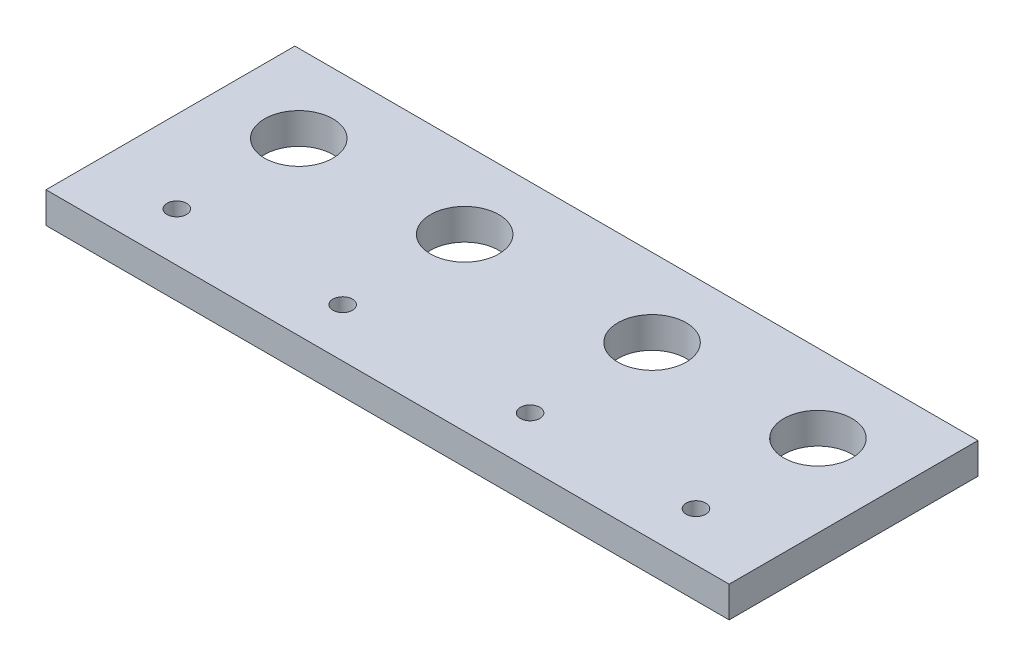
SolidWorks part; units mm, degrees
ref_plane "Front" through (0, 0, 0) normal (0, 0, 1) x (1, 0, 0)
ref_plane "Top" through (0, 0, 0) normal (0, 1, 0) x (1, 0, 0)
ref_plane "Right" through (0, 0, 0) normal (1, 0, 0) x (0, 0, -1)
sketch "Sketch1" plane through (0, 0, 0) normal (0, 1, 0) x (1, 0, 0)
  line L0 (0, -16) -> (19.2, -16)
  line L1 (-70, 0) -> (70, 0)
  line L2 (0, 0) -> (0, -32)
  line L3 (-70, -32) -> (70, -32)
  line L4 (70, 0) -> (70, -32)
  line L5 (19.2, -16) -> (53.2, -16)
  line L6 (-70, 0) -> (-70, -32)
  line L7 (-53.2, -16) -> (-53.2, -41)
  line L8 (-19.2, -16) -> (-19.2, -41)
  line L9 (19.2, -16) -> (19.2, -41)
  line L10 (53.2, -16) -> (53.2, -41)
  line L11 (-53.2, -41) -> (-53.2, -61)
  line L12 (-19.2, -41) -> (-19.2, -61)
  line L13 (19.2, -41) -> (19.2, -61)
  line L14 (53.2, -41) -> (53.2, -61)
  line L15 (-70, -32) -> (-70, -80)
  line L16 (-70, -80) -> (70, -80)
  line L17 (70, -80) -> (70, -32)
  line L18 (-53.2, -51) -> (-70, -51)
  line L19 (-70, -51) -> (70, -51)
  circle A0 centre (19.2, -16) radius 7
  circle A1 centre (53.2, -16) radius 7
  circle A2 centre (-53.2, -16) radius 7
  circle A3 centre (-19.2, -16) radius 7
  circle A4 centre (-53.2, -41) radius 2
  circle A5 centre (-53.2, -61) radius 2
  circle A6 centre (-19.2, -61) radius 2
  circle A7 centre (-19.2, -41) radius 2
  circle A12 centre (19.2, -41) radius 2
  circle A13 centre (19.2, -61) radius 2
  circle A14 centre (53.2, -61) radius 2
  circle A15 centre (53.2, -41) radius 2
  dimension "D3" = 19.2
  dimension "D7" = 48
  dimension "D1" = 70
  dimension "D2" = 32
  dimension "D4" = 34
  dimension "D5" = 25
  dimension "D6" = 20
extrude "Boss-Extrude1" add sketch "Sketch1" along normal blind 6.35
